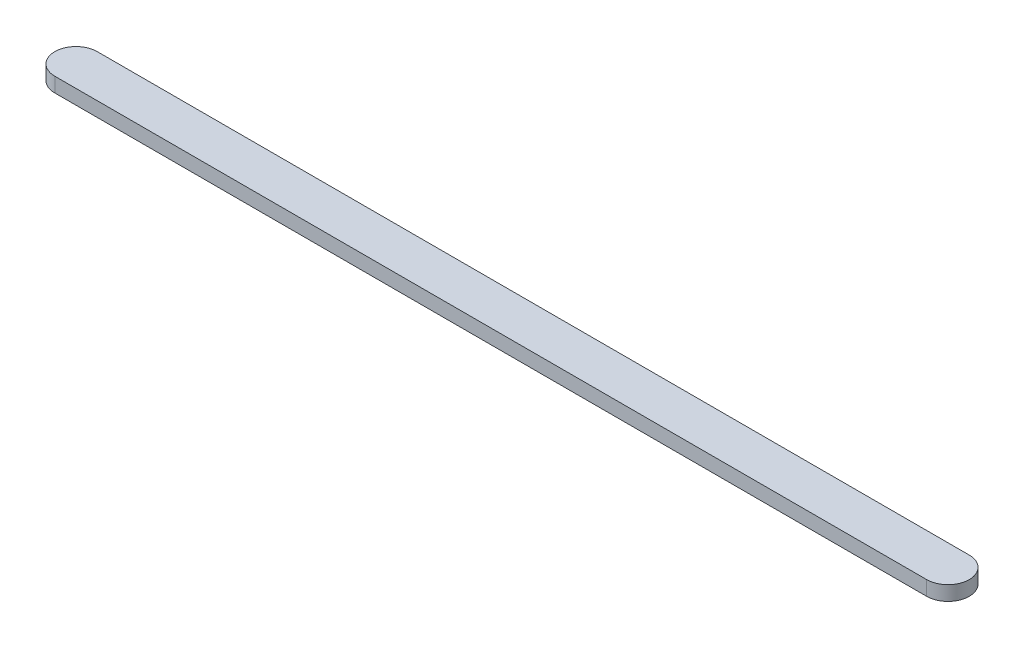
SolidWorks part; units mm, degrees
ref_plane "Front Plane" through (0, 0, 0) normal (0, 0, 1) x (1, 0, 0)
ref_plane "Top Plane" through (0, 0, 0) normal (0, 1, 0) x (1, 0, 0)
ref_plane "Right Plane" through (0, 0, 0) normal (1, 0, 0) x (0, 0, -1)
sketch "Sketch1" plane through (0, 0, 0) normal (0, 1, 0) x (1, 0, 0)
  line L0 (0, 0) -> (152.4, 0) construction
  line L1 (0, 3.7166) -> (152.4, 3.7166)
  line L2 (0, -3.7166) -> (152.4, -3.7166)
  arc A0 (0, 3.7166) -> (0, -3.7166) centre (0, 0) ccw
  arc A1 (152.4, -3.7166) -> (152.4, 3.7166) centre (152.4, 0) ccw
  point P3 (76.2, 0)
  dimension "D1" = 152.4
extrude "Boss-Extrude1" add sketch "Sketch1" along normal blind 2.54
sketch "Sketch2" [suppressed] plane through (0, 2.54, 0) normal (0, 1, 0) x (1, 0, 0)
  circle A0 centre (0, 0) radius 19.4961
extrude "Cut-Extrude1" [suppressed] cut sketch "Sketch2" against normal blind 24.13
